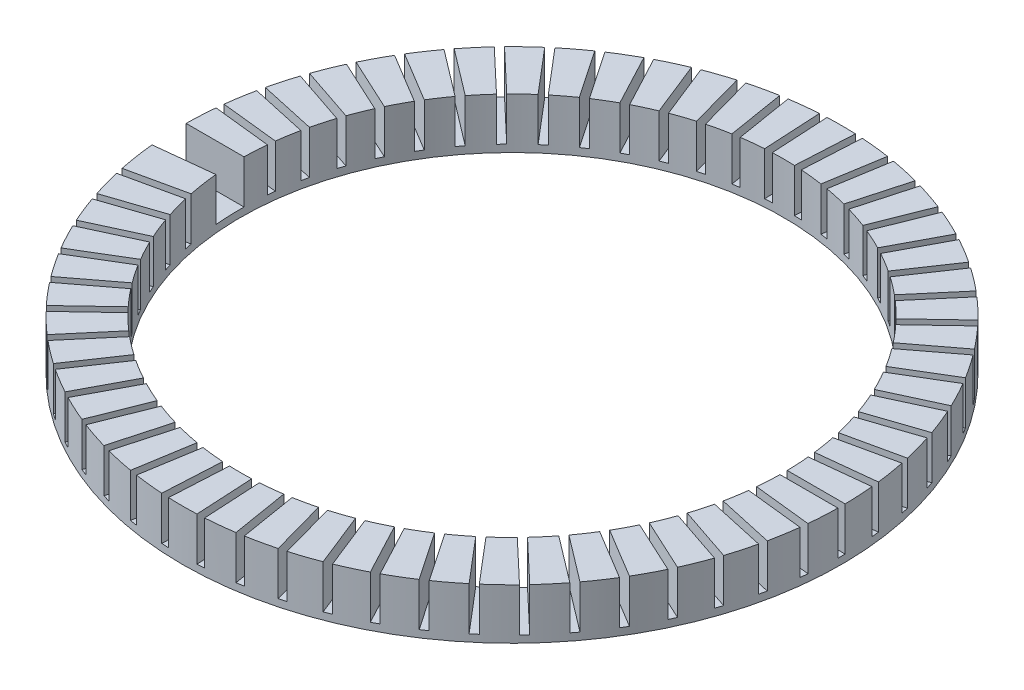
SolidWorks part; units mm, degrees
material "AISI 316 Stainless Steel Sheet (SS)"
ref_plane "Front Plane" through (0, 0, 0) normal (0, 0, 1) x (1, 0, 0)
ref_plane "Top Plane" through (0, 0, 0) normal (0, 1, 0) x (1, 0, 0)
ref_plane "Right Plane" through (0, 0, 0) normal (1, 0, 0) x (0, 0, -1)
sketch "Sketch1" plane through (0, 0, 0) normal (0, 1, 0) x (1, 0, 0)
  line L0 (-1000, 0) -> (-187.5, 0) construction
  line L1 (0, -1000) -> (0, -187.5) construction
  line L2 (-224.0438, -39.505) -> (-184.6515, -32.559) construction
  line L3 (-213.7801, 77.8096) -> (-176.1924, 64.1288) construction
  line L4 (-224.0438, 39.505) -> (-184.6515, 32.559) construction
  line L5 (-197.0208, 113.75) -> (-162.3798, 93.75) construction
  line L6 (-174.2751, 146.2342) -> (-143.6333, 120.5227) construction
  line L7 (-146.2342, 174.2751) -> (-120.5227, 143.6333) construction
  line L8 (-113.75, 197.0208) -> (-93.75, 162.3798) construction
  line L9 (-77.8096, 213.7801) -> (-64.1288, 176.1924) construction
  line L10 (-39.505, 224.0438) -> (-32.559, 184.6515) construction
  line L11 (39.505, 224.0438) -> (32.559, 184.6515) construction
  line L12 (77.8096, 213.7801) -> (64.1288, 176.1924) construction
  line L13 (113.75, 197.0208) -> (93.75, 162.3798) construction
  line L14 (146.2342, 174.2751) -> (120.5227, 143.6333) construction
  line L15 (174.2751, 146.2342) -> (143.6333, 120.5227) construction
  line L16 (197.0208, 113.75) -> (162.3798, 93.75) construction
  line L17 (213.7801, 77.8096) -> (176.1924, 64.1288) construction
  line L18 (120.5227, -143.6333) -> (146.2342, -174.2751) construction
  line L19 (143.6333, -120.5227) -> (174.2751, -146.2342) construction
  line L20 (162.3798, -93.75) -> (197.0208, -113.75) construction
  line L21 (176.1924, -64.1288) -> (213.7801, -77.8096) construction
  line L22 (184.6515, -32.559) -> (224.0438, -39.505) construction
  line L23 (187.5, 0) -> (49000, 0) construction
  line L24 (184.6515, 32.559) -> (224.0438, 39.505) construction
  line L25 (-176.1924, -64.1288) -> (-213.7801, -77.8096) construction
  line L26 (-162.3798, -93.75) -> (-197.0208, -113.75) construction
  line L27 (-143.6333, -120.5227) -> (-174.2751, -146.2342) construction
  line L28 (-120.5227, -143.6333) -> (-146.2342, -174.2751) construction
  line L29 (-93.75, -162.3798) -> (-113.75, -197.0208) construction
  line L30 (-64.1288, -176.1924) -> (-77.8096, -213.7801) construction
  line L31 (-32.559, -184.6515) -> (-39.505, -224.0438) construction
  line L32 (0, 187.5) -> (0, 49000) construction
  line L33 (32.559, -184.6515) -> (39.505, -224.0438) construction
  line L34 (64.1288, -176.1924) -> (77.8096, -213.7801) construction
  line L35 (93.75, -162.3798) -> (113.75, -197.0208) construction
  circle A0 centre (0, 0) radius 227.5
  circle A1 centre (0, 0) radius 187.5
  dimension "D1" = 455
  dimension "D19" = 375
  dimension "D22" = 40
  dimension "D2" = 10
  dimension "D3" = 10
  dimension "D4" = 10
  dimension "D5" = 10
  dimension "D6" = 10
  dimension "D7" = 10
  dimension "D8" = 10
  dimension "D9" = 10
  dimension "D10" = 10
  dimension "D11" = 10
  dimension "D12" = 10
  dimension "D13" = 10
  dimension "D14" = 10
  dimension "D15" = 10
  dimension "D16" = 10
  dimension "D17" = 10
  dimension "D18" = 10
extrude "Boss-Extrude1" add sketch "Sketch1" along normal mid plane 5
sketch "Sketch2" plane through (0, 2.5, 0) normal (0, 1, 0) x (1, 0, 0)
  line L0 (-1000, 0) -> (49000, 0) construction
  line L1 (0, -1000) -> (0, 49000) construction
  line L2 (-227.4863, 2.5) -> (-187.4833, 2.5)
  line L3 (137.8313, -127.1172) -> (166.8733, -154.6272)
  line L4 (-187.4833, -2.5) -> (-227.4863, -2.5)
  line L5 (-186.6546, 17.7852) -> (-226.423, 22.1102)
  line L6 (-225.8824, 27.0809) -> (-186.114, 22.7559)
  line L7 (-183.6375, 37.8618) -> (-222.7052, 46.4613)
  line L8 (-221.6303, 51.3444) -> (-182.5627, 42.7449)
  line L9 (-178.4674, 57.4946) -> (-216.3763, 70.2676)
  line L10 (-214.7798, 75.0058) -> (-176.8709, 62.2328)
  line L11 (-171.205, 76.4533) -> (-207.5107, 93.2501)
  line L12 (-205.4112, 97.7879) -> (-169.1055, 80.9911)
  line L13 (-161.9353, 94.5156) -> (-196.2121, 115.1393)
  line L14 (-193.6344, 119.4236) -> (-159.3576, 98.7999)
  line L15 (-150.7671, 111.4698) -> (-182.6132, 135.6786)
  line L16 (-179.5873, 139.6591) -> (-147.7412, 115.4503)
  line L17 (-137.8313, 127.1172) -> (-166.8733, 154.6272)
  line L18 (-163.4348, 158.2572) -> (-134.3928, 130.7472)
  line L19 (-123.2795, 141.2742) -> (-149.1769, 171.7629)
  line L20 (-145.3661, 174.9999) -> (-119.4687, 144.5111)
  line L21 (-107.2824, 153.7749) -> (-129.7316, 186.8849)
  line L22 (-125.5931, 189.6908) -> (-103.144, 156.5809)
  line L23 (-90.0276, 164.4728) -> (-108.7653, 199.8158)
  line L24 (-104.3477, 202.1579) -> (-85.61, 166.8148)
  line L25 (-71.7172, 173.2423) -> (-86.5238, 210.4041)
  line L26 (-81.8789, 212.2548) -> (-67.0723, 175.093)
  line L27 (-52.566, 179.9807) -> (-63.2679, 218.5256)
  line L28 (-58.4501, 219.8632) -> (-47.7482, 181.3184)
  line L29 (-32.7985, 184.6091) -> (-39.2702, 224.085)
  line L30 (-34.3361, 224.8939) -> (-27.8644, 185.418)
  line L31 (-12.6465, 187.073) -> (-14.8122, 227.0173)
  line L32 (-9.8195, 227.288) -> (-7.6538, 187.3437)
  line L33 (7.6538, 187.3437) -> (9.8195, 227.288)
  line L34 (14.8122, 227.0173) -> (12.6465, 187.073)
  line L35 (27.8644, 185.418) -> (34.3361, 224.8939)
  line L36 (39.2702, 224.085) -> (32.7985, 184.6091)
  line L37 (47.7482, 181.3184) -> (58.4501, 219.8632)
  line L38 (63.2679, 218.5256) -> (52.566, 179.9807)
  line L39 (67.0723, 175.093) -> (81.8789, 212.2548)
  line L40 (86.5238, 210.4041) -> (71.7172, 173.2423)
  line L41 (85.61, 166.8148) -> (104.3477, 202.1579)
  line L42 (108.7653, 199.8158) -> (90.0276, 164.4728)
  line L43 (103.144, 156.5809) -> (125.5931, 189.6908)
  line L44 (129.7316, 186.8849) -> (107.2824, 153.7749)
  line L45 (119.4687, 144.5111) -> (145.3661, 174.9999)
  line L46 (149.1769, 171.7629) -> (123.2795, 141.2742)
  line L47 (134.3928, 130.7472) -> (163.4348, 158.2572)
  line L48 (166.8733, 154.6272) -> (137.8313, 127.1172)
  line L49 (147.7412, 115.4503) -> (179.5873, 139.6591)
  line L50 (182.6132, 135.6786) -> (150.7671, 111.4698)
  line L51 (159.3576, 98.7999) -> (193.6344, 119.4236)
  line L52 (196.2121, 115.1393) -> (161.9353, 94.5156)
  line L53 (169.1055, 80.9911) -> (205.4112, 97.7879)
  line L54 (207.5107, 93.2501) -> (171.205, 76.4533)
  line L55 (176.8709, 62.2328) -> (214.7798, 75.0058)
  line L56 (216.3763, 70.2676) -> (178.4674, 57.4946)
  line L57 (182.5627, 42.7449) -> (221.6303, 51.3444)
  line L58 (222.7052, 46.4613) -> (183.6375, 37.8618)
  line L59 (186.114, 22.7559) -> (225.8824, 27.0809)
  line L60 (226.423, 22.1102) -> (186.6546, 17.7852)
  line L61 (187.4833, 2.5) -> (227.4863, 2.5)
  line L62 (227.4863, -2.5) -> (187.4833, -2.5)
  line L63 (186.6546, -17.7852) -> (226.423, -22.1102)
  line L64 (225.8824, -27.0809) -> (186.114, -22.7559)
  line L65 (183.6375, -37.8618) -> (222.7052, -46.4613)
  line L66 (221.6303, -51.3444) -> (182.5627, -42.7449)
  line L67 (178.4674, -57.4946) -> (216.3763, -70.2676)
  line L68 (214.7798, -75.0058) -> (176.8709, -62.2328)
  line L69 (171.205, -76.4533) -> (207.5107, -93.2501)
  line L70 (205.4112, -97.7879) -> (169.1055, -80.9911)
  line L71 (161.9353, -94.5156) -> (196.2121, -115.1393)
  line L72 (193.6344, -119.4236) -> (159.3576, -98.7999)
  line L73 (150.7671, -111.4698) -> (182.6132, -135.6786)
  line L74 (179.5873, -139.6591) -> (147.7412, -115.4503)
  line L75 (163.4348, -158.2572) -> (134.3928, -130.7472)
  line L76 (123.2795, -141.2742) -> (149.1769, -171.7629)
  line L77 (145.3661, -174.9999) -> (119.4687, -144.5111)
  line L78 (107.2824, -153.7749) -> (129.7316, -186.8849)
  line L79 (125.5931, -189.6908) -> (103.144, -156.5809)
  line L80 (90.0276, -164.4728) -> (108.7653, -199.8158)
  line L81 (104.3477, -202.1579) -> (85.61, -166.8148)
  line L82 (71.7172, -173.2423) -> (86.5238, -210.4041)
  line L83 (81.8789, -212.2548) -> (67.0723, -175.093)
  line L84 (52.566, -179.9807) -> (63.2679, -218.5256)
  line L85 (58.4501, -219.8632) -> (47.7482, -181.3184)
  line L86 (32.7985, -184.6091) -> (39.2702, -224.085)
  line L87 (34.3361, -224.8939) -> (27.8644, -185.418)
  line L88 (12.6465, -187.073) -> (14.8122, -227.0173)
  line L89 (9.8195, -227.288) -> (7.6538, -187.3437)
  line L90 (-7.6538, -187.3437) -> (-9.8195, -227.288)
  line L91 (-14.8122, -227.0173) -> (-12.6465, -187.073)
  line L92 (-27.8644, -185.418) -> (-34.3361, -224.8939)
  line L93 (-39.2702, -224.085) -> (-32.7985, -184.6091)
  line L94 (-47.7482, -181.3184) -> (-58.4501, -219.8632)
  line L95 (-63.2679, -218.5256) -> (-52.566, -179.9807)
  line L96 (-67.0723, -175.093) -> (-81.8789, -212.2548)
  line L97 (-86.5238, -210.4041) -> (-71.7172, -173.2423)
  line L98 (-85.61, -166.8148) -> (-104.3477, -202.1579)
  line L99 (-108.7653, -199.8158) -> (-90.0276, -164.4728)
  line L100 (-103.144, -156.5809) -> (-125.5931, -189.6908)
  line L101 (-129.7316, -186.8849) -> (-107.2824, -153.7749)
  line L102 (-119.4687, -144.5111) -> (-145.3661, -174.9999)
  line L103 (-149.1769, -171.7629) -> (-123.2795, -141.2742)
  line L104 (-134.3928, -130.7472) -> (-163.4348, -158.2572)
  line L105 (-166.8733, -154.6272) -> (-137.8313, -127.1172)
  line L106 (-147.7412, -115.4503) -> (-179.5873, -139.6591)
  line L107 (-182.6132, -135.6786) -> (-150.7671, -111.4698)
  line L108 (-159.3576, -98.7999) -> (-193.6344, -119.4236)
  line L109 (-196.2121, -115.1393) -> (-161.9353, -94.5156)
  line L110 (-169.1055, -80.9911) -> (-205.4112, -97.7879)
  line L111 (-207.5107, -93.2501) -> (-171.205, -76.4533)
  line L112 (-176.8709, -62.2328) -> (-214.7798, -75.0058)
  line L113 (-216.3763, -70.2676) -> (-178.4674, -57.4946)
  line L114 (-182.5627, -42.7449) -> (-221.6303, -51.3444)
  line L115 (-222.7052, -46.4613) -> (-183.6375, -37.8618)
  line L116 (-186.114, -22.7559) -> (-225.8824, -27.0809)
  line L117 (-226.423, -22.1102) -> (-186.6546, -17.7852)
  arc A0 (150.7671, -111.4698) -> (159.3576, -98.7999) centre (0, 0) ccw
  arc A1 (182.6132, -135.6786) -> (193.6344, -119.4236) centre (0, 0) ccw
  arc A2 (196.2121, -115.1393) -> (205.4112, -97.7879) centre (0, 0) ccw
  arc A3 (161.9353, -94.5156) -> (169.1055, -80.9911) centre (0, 0) ccw
  arc A4 (207.5107, -93.2501) -> (214.7798, -75.0058) centre (0, 0) ccw
  arc A5 (171.205, -76.4533) -> (176.8709, -62.2328) centre (0, 0) ccw
  arc A6 (178.4674, -57.4946) -> (182.5627, -42.7449) centre (0, 0) ccw
  arc A7 (216.3763, -70.2676) -> (221.6303, -51.3444) centre (0, 0) ccw
  arc A8 (183.6375, -37.8618) -> (186.114, -22.7559) centre (0, 0) ccw
  arc A9 (222.7052, -46.4613) -> (225.8824, -27.0809) centre (0, 0) ccw
  arc A10 (186.6546, -17.7852) -> (187.4833, -2.5) centre (0, 0) ccw
  arc A11 (226.423, -22.1102) -> (227.4863, -2.5) centre (0, 0) ccw
  arc A12 (227.4863, 2.5) -> (226.423, 22.1102) centre (0, 0) ccw
  arc A13 (187.4833, 2.5) -> (186.6546, 17.7852) centre (0, 0) ccw
  arc A14 (186.114, 22.7559) -> (183.6375, 37.8618) centre (0, 0) ccw
  arc A15 (225.8824, 27.0809) -> (222.7052, 46.4613) centre (0, 0) ccw
  arc A16 (221.6303, 51.3444) -> (216.3763, 70.2676) centre (0, 0) ccw
  arc A17 (182.5627, 42.7449) -> (178.4674, 57.4946) centre (0, 0) ccw
  arc A18 (214.7798, 75.0058) -> (207.5107, 93.2501) centre (0, 0) ccw
  arc A19 (176.8709, 62.2328) -> (171.205, 76.4533) centre (0, 0) ccw
  arc A20 (169.1055, 80.9911) -> (161.9353, 94.5156) centre (0, 0) ccw
  arc A21 (205.4112, 97.7879) -> (196.2121, 115.1393) centre (0, 0) ccw
  arc A22 (193.6344, 119.4236) -> (182.6132, 135.6786) centre (0, 0) ccw
  arc A23 (159.3576, 98.7999) -> (150.7671, 111.4698) centre (0, 0) ccw
  arc A24 (147.7412, 115.4503) -> (137.8313, 127.1172) centre (0, 0) ccw
  arc A25 (179.5873, 139.6591) -> (166.8733, 154.6272) centre (0, 0) ccw
  arc A26 (134.3928, 130.7472) -> (123.2795, 141.2742) centre (0, 0) ccw
  arc A27 (163.4348, 158.2572) -> (149.1769, 171.7629) centre (0, 0) ccw
  arc A28 (119.4687, 144.5111) -> (107.2824, 153.7749) centre (0, 0) ccw
  arc A29 (145.3661, 174.9999) -> (129.7316, 186.8849) centre (0, 0) ccw
  arc A30 (103.144, 156.5809) -> (90.0276, 164.4728) centre (0, 0) ccw
  arc A31 (125.5931, 189.6908) -> (108.7653, 199.8158) centre (0, 0) ccw
  arc A32 (85.61, 166.8148) -> (71.7172, 173.2423) centre (0, 0) ccw
  arc A33 (104.3477, 202.1579) -> (86.5238, 210.4041) centre (0, 0) ccw
  arc A34 (67.0723, 175.093) -> (52.566, 179.9807) centre (0, 0) ccw
  arc A35 (81.8789, 212.2548) -> (63.2679, 218.5256) centre (0, 0) ccw
  arc A36 (47.7482, 181.3184) -> (32.7985, 184.6091) centre (0, 0) ccw
  arc A37 (58.4501, 219.8632) -> (39.2702, 224.085) centre (0, 0) ccw
  arc A38 (27.8644, 185.418) -> (12.6465, 187.073) centre (0, 0) ccw
  arc A39 (34.3361, 224.8939) -> (14.8122, 227.0173) centre (0, 0) ccw
  arc A40 (7.6538, 187.3437) -> (-7.6538, 187.3437) centre (0, 0) ccw
  arc A41 (9.8195, 227.288) -> (-9.8195, 227.288) centre (0, 0) ccw
  arc A42 (-12.6465, 187.073) -> (-27.8644, 185.418) centre (0, 0) ccw
  arc A43 (-14.8122, 227.0173) -> (-34.3361, 224.8939) centre (0, 0) ccw
  arc A44 (-39.2702, 224.085) -> (-58.4501, 219.8632) centre (0, 0) ccw
  arc A45 (-32.7985, 184.6091) -> (-47.7482, 181.3184) centre (0, 0) ccw
  arc A46 (-52.566, 179.9807) -> (-67.0723, 175.093) centre (0, 0) ccw
  arc A47 (-63.2679, 218.5256) -> (-81.8789, 212.2548) centre (0, 0) ccw
  arc A48 (-86.5238, 210.4041) -> (-104.3477, 202.1579) centre (0, 0) ccw
  arc A49 (-71.7172, 173.2423) -> (-85.61, 166.8148) centre (0, 0) ccw
  arc A50 (-90.0276, 164.4728) -> (-103.144, 156.5809) centre (0, 0) ccw
  arc A51 (-108.7653, 199.8158) -> (-125.5931, 189.6908) centre (0, 0) ccw
  arc A52 (-129.7316, 186.8849) -> (-145.3661, 174.9999) centre (0, 0) ccw
  arc A53 (-107.2824, 153.7749) -> (-119.4687, 144.5111) centre (0, 0) ccw
  arc A54 (-123.2795, 141.2742) -> (-134.3928, 130.7472) centre (0, 0) ccw
  arc A55 (-149.1769, 171.7629) -> (-163.4348, 158.2572) centre (0, 0) ccw
  arc A56 (-166.8733, 154.6272) -> (-179.5873, 139.6591) centre (0, 0) ccw
  arc A57 (-137.8313, 127.1172) -> (-147.7412, 115.4503) centre (0, 0) ccw
  arc A58 (-182.6132, 135.6786) -> (-193.6344, 119.4236) centre (0, 0) ccw
  arc A59 (-150.7671, 111.4698) -> (-159.3576, 98.7999) centre (0, 0) ccw
  arc A60 (-196.2121, 115.1393) -> (-205.4112, 97.7879) centre (0, 0) ccw
  arc A61 (-161.9353, 94.5156) -> (-169.1055, 80.9911) centre (0, 0) ccw
  arc A62 (-171.205, 76.4533) -> (-176.8709, 62.2328) centre (0, 0) ccw
  arc A63 (-207.5107, 93.2501) -> (-214.7798, 75.0058) centre (0, 0) ccw
  arc A64 (-216.3763, 70.2676) -> (-221.6303, 51.3444) centre (0, 0) ccw
  arc A65 (-178.4674, 57.4946) -> (-182.5627, 42.7449) centre (0, 0) ccw
  arc A66 (-183.6375, 37.8618) -> (-187.4833, 2.5) centre (0, 0) ccw
  arc A67 (-222.7052, 46.4613) -> (-227.4863, 2.5) centre (0, 0) ccw
  arc A68 (-187.4833, -2.5) -> (147.7412, -115.4503) centre (0, 0) ccw
  arc A69 (-227.4863, -2.5) -> (179.5873, -139.6591) centre (0, 0) ccw
  point P155 (0, 0)
  circle M7 centre (0, 0) radius 227.5
  circle M8 centre (0, 0) radius 187.5
  dimension "D1" = 455
  dimension "D2" = 375
  dimension "D5" = 15.3076
  dimension "D3" = 5
  dimension "D6" = 15.2852
  dimension "D7" = 19.6102
  dimension "D4" = 58
extrude "Boss-Extrude2" add sketch "Sketch2" along normal blind 30 contours L5 L2 M8 M7 | L7 L6 M8 M7 | L9 L8 M8 M7 | L11 L10 M8 M7 | L13 L12 M8 M7 | L15 L14 M8 M7 | L17 L16 M8 M7 | L19 L18 M8 M7 | L21 L20 M8 M7 | L74 L4 M7 M8 | L73 L72 M8 M7 | L71 L70 M8 M7 | L69 L68 M8 M7 | L67 L66 M8 M7 | L65 L64 M8 M7 | L63 L62 M8 M7 | L61 L60 M8 M7 | L59 L58 M8 M7 | L57 L56 M8 M7 | L55 L54 M8 M7 | L53 L52 M8 M7 | L51 L50 M8 M7 | L49 L48 M8 M7 | L47 L46 M8 M7 | L45 L44 M8 M7 | L43 L42 M8 M7 | L41 L40 M8 M7 | L39 L38 M8 M7 | L37 L36 M8 M7 | L35 L34 M8 M7 | L33 L32 M8 M7 | L31 L30 M8 M7 | L29 L28 M8 M7 | L27 L26 M8 M7 | L25 L24 M8 M7 | L23 L22 M8 M7 | L96 L95 M8 M7 | L94 L93 M8 M7 | L92 L91 M8 M7 | L90 L89 M8 M7 | L88 L87 M8 M7 | L86 L85 M8 M7 | L84 L83 M8 M7 | L82 L81 M8 M7 | L80 L79 M8 M7 | L78 L77 M8 M7 | L76 L75 M8 M7 | L74 L3 M7 M8 | L116 L115 M8 M7 | L114 L113 M8 M7 | L112 L111 M8 M7 | L110 L109 M8 M7 | L108 L107 M8 M7 | L106 L105 M8 M7 | L104 L103 M8 M7 | L102 L101 M8 M7 | L100 L99 M8 M7 | L98 L97 M8 M7
